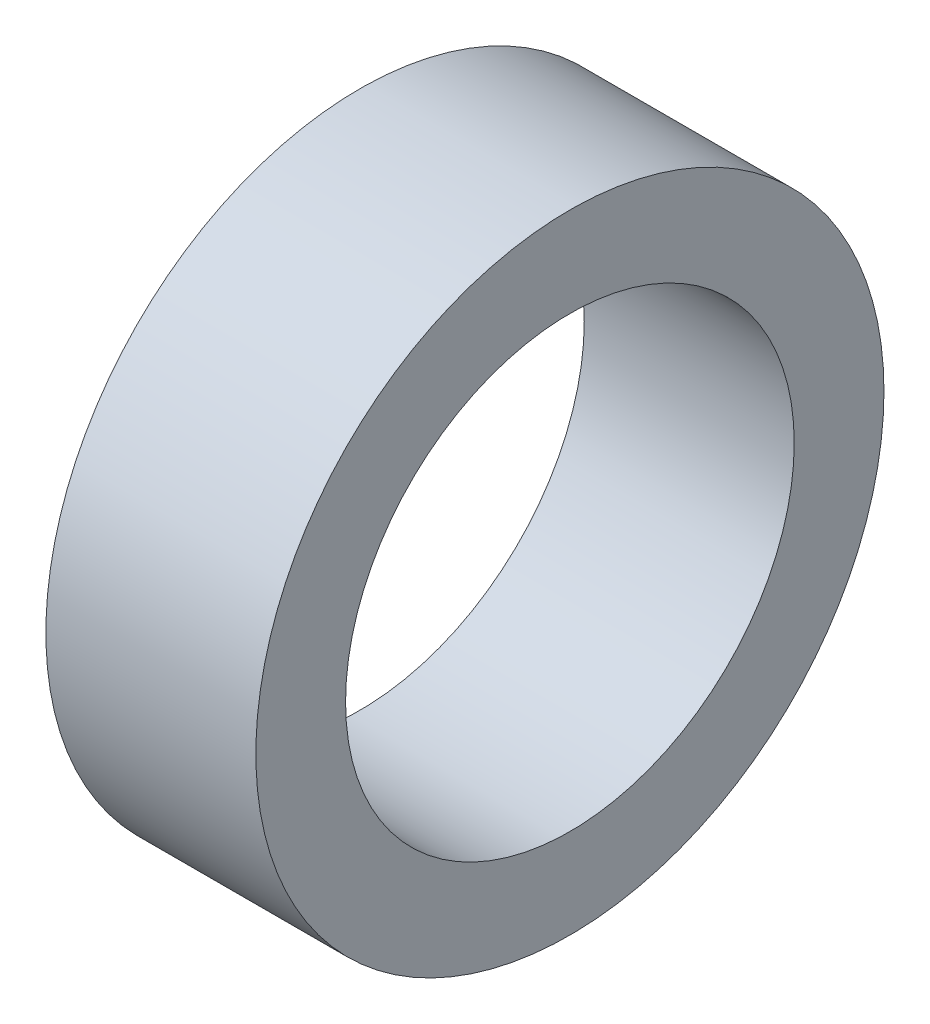
SolidWorks part; units mm, degrees
ref_plane "Front Plane" through (0, 0, 0) normal (1, 0, 0) x (0, 1, 0)
ref_plane "Top Plane" through (0, 0, 0) normal (0, 0, 1) x (0, 1, 0)
ref_plane "Right Plane" through (0, 0, 0) normal (0, 1, 0) x (-1, 0, 0)
sketch "Sketch1" plane through (0, 0, 0) normal (1, 0, 0) x (0, 1, 0)
  circle A0 centre (0, 0) radius 4.445
  circle A1 centre (0, 0) radius 3.175
  dimension "D1" = 6.35
  dimension "D2" = 8.89
extrude "Boss-Extrude1" add sketch "Sketch1" along normal blind 2.9718
